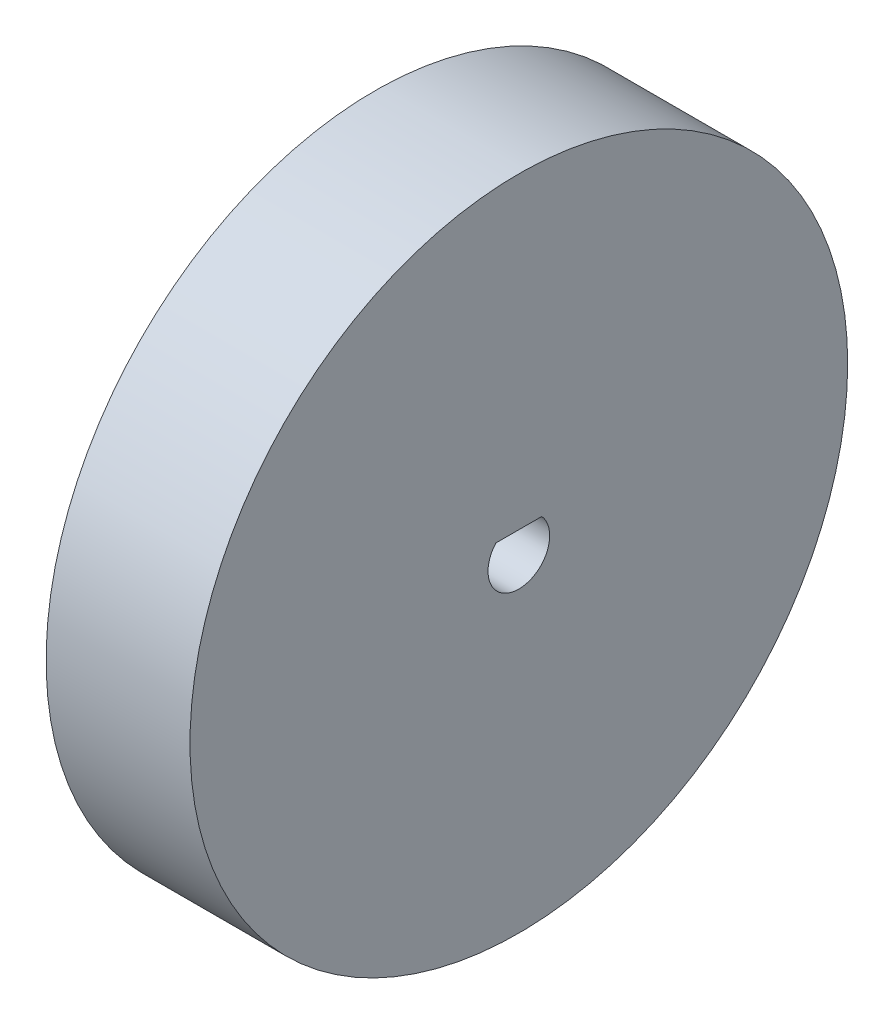
SolidWorks part; units mm, degrees
ref_plane "Plan de face" through (0, 0, 0) normal (0, 0, 1) x (1, 0, 0)
ref_plane "Plan de dessus" through (0, 0, 0) normal (0, 1, 0) x (1, 0, 0)
ref_plane "Plan de droite" through (0, 0, 0) normal (1, 0, 0) x (0, 0, -1)
sketch "Esquisse1" plane through (0, 0, 0) normal (1, 0, 0) x (0, 0, -1)
  line L0 (-1.118, 1) -> (1.118, 1)
  circle A0 centre (0, 0) radius 16
  circle A1 centre (0, 0) radius 1.5 construction
  arc A2 (-1.118, 1) -> (1.118, 1) centre (0, 0) ccw
  dimension "D1" = 32
  dimension "D2" = 3
  dimension "D3" = 1
extrude "Boss.-Extru.1" add sketch "Esquisse1" along normal blind 7
